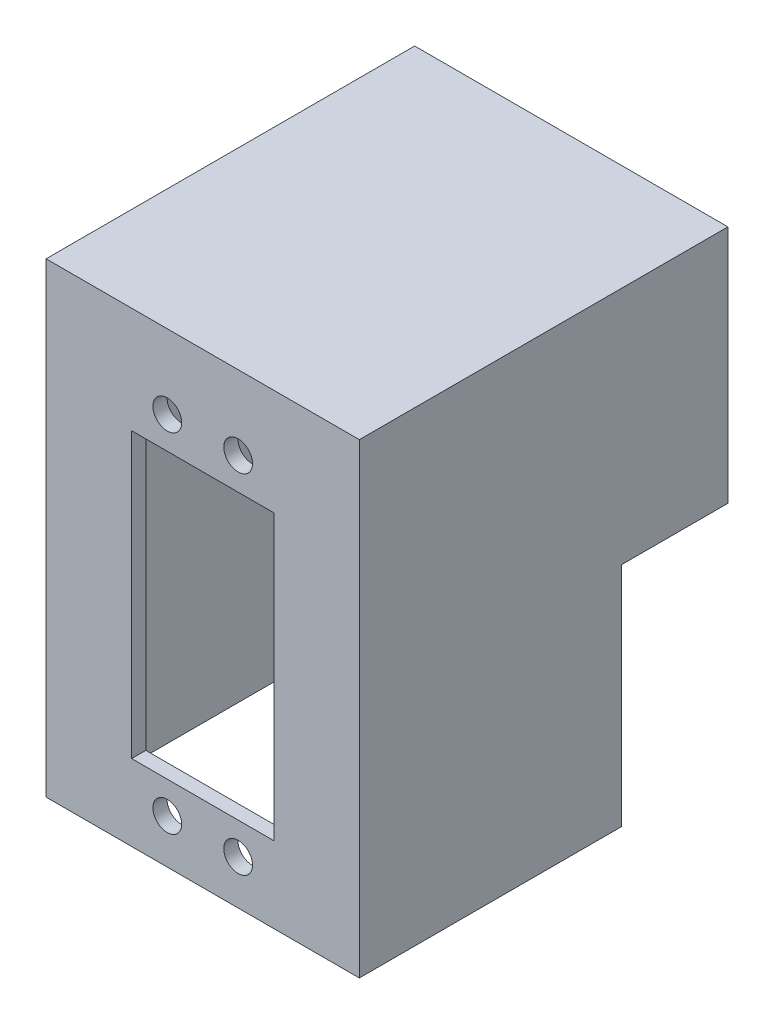
SolidWorks part; units mm, degrees
ref_plane "Front Plane" through (0, 0, 0) normal (0, 0, 1) x (1, 0, 0)
ref_plane "Top Plane" through (0, 0, 0) normal (0, 1, 0) x (1, 0, 0)
ref_plane "Right Plane" through (0, 0, 0) normal (1, 0, 0) x (0, 0, -1)
sketch "Sketch1" plane through (0, 0, 0) normal (0, 1, 0) x (1, 0, 0)
  line L1 (-90, 30) -> (90, 30)
  line L2 (-90, 30) -> (-90, -30)
  line L3 (-90, -30) -> (90, -30)
  line L4 (90, 30) -> (90, -30)
  line L5 (-90, 30) -> (90, -30) construction
  line L6 (-90, -30) -> (90, 30) construction
  point P0 (0, 0)
  dimension "D1" = 60
  dimension "D2" = 180
extrude "Extrude-Thin1" add sketch "Sketch1" along normal blind 30 thin thin type one direction wall 2
sketch "Sketch3" plane through (0, 30, 0) normal (0, 1, 0) x (1, 0, 0)
  line L0 (-92, -32) -> (92, -32) construction
  line L1 (-92, 32) -> (92, 32)
  line L2 (-92, 32) -> (-92, -32)
  line L3 (-92, -32) -> (92, -32)
  line L4 (92, 32) -> (92, -32)
extrude "Boss-Extrude1" add sketch "Sketch3" along normal blind 2
sketch "Sketch4" plane through (0, 32, 0) normal (0, 1, 0) x (1, 0, 0)
  line L0 (-92, 32) -> (-92, -32) construction
  line L1 (-92, -32) -> (-92, 0) construction
  line L2 (-92, 0) -> (-92, -16) construction
  line L3 (-92, -16) -> (-92, -8) construction
  line L4 (-92, -8) -> (92, -8) construction
  line L5 (92, -32) -> (92, 32) construction
  line L6 (92, -8) -> (-92, -8) construction
  line L7 (-92, -8) -> (-92, 0) construction
  line L8 (-92, 0) -> (92, 0) construction
  line L9 (92, 0) -> (92, -8) construction
  line L10 (92, -8) -> (92, -4) construction
  line L11 (92, -4) -> (92, 0) construction
  line L12 (92, 0) -> (92, -2) construction
  line L13 (92, -2) -> (-92, -2) construction
  line L14 (-92, -2) -> (-92, -4) construction
  line L15 (-92, -4) -> (92, -4) construction
  line L17 (-87.2097, 0) -> (87.2097, 0)
  line L18 (-87.2097, 0) -> (-87.2097, -4)
  line L19 (-87.2097, -4) -> (87.2097, -4)
  line L20 (87.2097, 0) -> (87.2097, -4)
  line L21 (-87.2097, 0) -> (87.2097, -4) construction
  line L22 (-87.2097, -4) -> (87.2097, 0) construction
  point P4 (0, -2)
extrude "Cut-Extrude1" cut sketch "Sketch4" against normal blind 5
sketch "Sketch5" plane through (0, 0, 32) normal (0, 0, 1) x (1, 0, 0)
  line L0 (0, 32) -> (0, 0) construction
  line L1 (-92, 32) -> (92, 32) construction
  line L3 (-20.0979, 45.5348) -> (20.0979, 45.5348)
  line L4 (-20.0979, 45.5348) -> (-20.0979, -13.5348)
  line L5 (-20.0979, -13.5348) -> (20.0979, -13.5348)
  line L6 (20.0979, 45.5348) -> (20.0979, -13.5348)
  line L7 (-20.0979, 45.5348) -> (20.0979, -13.5348) construction
  line L8 (-20.0979, -13.5348) -> (20.0979, 45.5348) construction
  point P5 (0, 16)
extrude "Cut-Extrude2" cut sketch "Sketch5" against normal blind 15
sketch "Sketch6" plane through (0, 0, 32) normal (0, 0, 1) x (1, 0, 0)
  line L1 (-20.0979, 63.7769) -> (20.0979, 63.7769)
  line L2 (-20.0979, 63.7769) -> (-20.0979, 0)
  line L3 (-20.0979, 0) -> (20.0979, 0)
  line L4 (20.0979, 63.7769) -> (20.0979, 0)
extrude "Extrude-Thin2" add sketch "Sketch6" along normal blind 35 and the other way up to surface thin other way up to face at (0, 31, 17) thin type one direction wall 2
sketch "Sketch7" plane through (0, 0, 0) normal (0, -1, 0) x (1, 0, 0)
  line L1 (-61.6448, 15.0511) -> (66.3737, 15.0511)
  line L2 (-61.6448, 15.0511) -> (-61.6448, 73.6559)
  line L3 (-61.6448, 73.6559) -> (66.3737, 73.6559)
  line L4 (66.3737, 15.0511) -> (66.3737, 73.6559)
extrude "Cut-Extrude3" cut sketch "Sketch7" along normal blind 85
sketch "Sketch8" plane through (-22.0979, 0, 0) normal (-1, 0, 0) x (0, 0, 1)
  line L1 (17, 30) -> (30, 30)
  line L2 (17, 30) -> (17, 0)
  line L3 (17, 0) -> (30, 0)
  line L4 (30, 30) -> (30, 0)
extrude "Cut-Extrude4" cut sketch "Sketch8" against normal blind 85
sketch "Sketch9" plane through (0, 0, 67) normal (0, 0, 1) x (1, 0, 0)
  line L0 (-22.0979, 65.7769) -> (-22.0979, 0) construction
  line L1 (-22.0979, 65.7769) -> (22.0979, 65.7769)
  line L2 (-22.0979, 65.7769) -> (-22.0979, 0)
  line L3 (-22.0979, 0) -> (22.0979, 0)
  line L4 (22.0979, 65.7769) -> (22.0979, 0)
  line L5 (22.0979, 65.7769) -> (-22.0979, 65.7769) construction
extrude "Boss-Extrude2" add sketch "Sketch9" along normal blind 2
sketch "Sketch13" plane through (0, 0, 69) normal (0, 0, 1) x (1, 0, 0)
  line L0 (0, 50.7769) -> (0, 10.7769) construction
  line L1 (22.0979, 65.7769) -> (-22.0979, 65.7769) construction
  line L3 (0, 65.7769) -> (0, 50.7769) construction
  line L4 (-10.03, 50.8069) -> (10.03, 50.8069)
  line L5 (-10.03, 50.8069) -> (-10.03, 10.7469)
  line L6 (-10.03, 10.7469) -> (10.03, 10.7469)
  line L7 (10.03, 50.8069) -> (10.03, 10.7469)
  line L8 (-10.03, 50.8069) -> (10.03, 10.7469) construction
  line L9 (-10.03, 10.7469) -> (10.03, 50.8069) construction
  point P1 (0, 30.7769)
  dimension "D1" = 15
  dimension "D2" = 40
  dimension "D3" = 20.06
  dimension "D4" = 40.06
extrude "Cut-Extrude6" cut sketch "Sketch13" against normal blind 10
sketch "Sketch18" plane through (0, 0, 69) normal (0, 0, 1) x (1, 0, 0)
  line L0 (0, 10.7469) -> (0, 0) construction
  line L1 (-10.03, 10.7469) -> (10.03, 10.7469) construction
  line L2 (0, 0) -> (0, 10.7469) construction
  line L3 (0, 10.7469) -> (0, 6.2469) construction
  line L4 (0, 6.2469) -> (-5, 6.2469) construction
  line L5 (0, 6.2469) -> (5, 6.2469) construction
  circle A0 centre (-5, 6.2469) radius 2.03
  circle A1 centre (5, 6.2469) radius 2.03
  dimension "D4" = 4.06
  dimension "D5" = 4.06
  dimension "D1" = 4.5
  dimension "D2" = 5
  dimension "D3" = 5
extrude "Cut-Extrude8" cut sketch "Sketch18" against normal blind 10
sketch "Sketch19" plane through (0, 0, 32) normal (0, 0, 1) x (1, 0, 0)
  line L0 (92, 0) -> (22.0979, 0) construction
  line L2 (32.0489, 20) -> (82.0489, 20)
  line L3 (32.0489, 20) -> (32.0489, -20)
  line L4 (32.0489, -20) -> (82.0489, -20)
  line L5 (82.0489, 20) -> (82.0489, -20)
  line L6 (32.0489, 20) -> (82.0489, -20) construction
  line L7 (32.0489, -20) -> (82.0489, 20) construction
  point P4 (57.0489, 0)
  dimension "D1" = 50
  dimension "D2" = 40
extrude "Cut-Extrude9" cut sketch "Sketch19" against normal blind 10
sketch "Sketch20" plane through (0, 0, 69) normal (0, 0, 1) x (1, 0, 0)
  line L0 (-10.03, 50.8069) -> (10.03, 50.8069) construction
  line L1 (10.03, 50.8069) -> (0, 50.8069) construction
  line L2 (0, 50.8069) -> (0, 55.3069) construction
  line L3 (0, 55.3069) -> (5, 55.3069) construction
  line L4 (0, 55.3069) -> (-5, 55.3069) construction
  circle A0 centre (-5, 55.3069) radius 2.03
  circle A1 centre (5, 55.3069) radius 2.03
  dimension "D4" = 4.06
  dimension "D5" = 4.06
  dimension "D1" = 4.5
  dimension "D2" = 5
  dimension "D3" = 5
extrude "Cut-Extrude10" cut sketch "Sketch20" against normal blind 10
sketch "Sketch21" plane through (-92, 0, 0) normal (-1, 0, 0) x (0, 0, 1)
  line L1 (-32, 32) -> (32, 32)
  line L2 (-32, 32) -> (-32, 0)
  line L3 (-32, 0) -> (32, 0)
  line L4 (32, 32) -> (32, 0)
extrude "Cut-Extrude11" cut sketch "Sketch21" against normal blind 217
